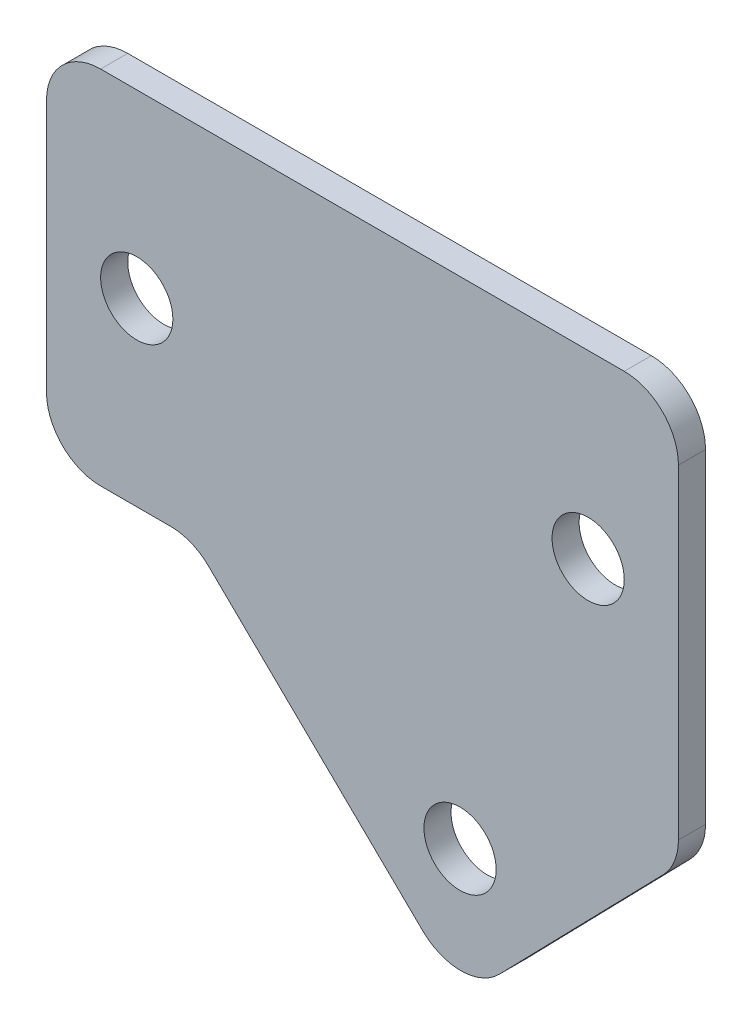
SolidWorks part; units mm, degrees
material "1060 合金"
ref_plane "正面" through (0, 0, 0) normal (0, 0, 1) x (1, 0, 0)
ref_plane "平面" through (0, 0, 0) normal (0, 1, 0) x (1, 0, 0)
ref_plane "右側面" through (0, 0, 0) normal (1, 0, 0) x (0, 0, -1)
sketch "ｽｹｯﾁ1" plane through (0, 0, 0) normal (0, 0, 1) x (1, 0, 0)
  line L0 (-17.5, 7.2592) -> (17.5, 7.2592) construction
  line L1 (-17.5, -17.2592) -> (17.5, -17.2592)
  line L2 (-17.5, -17.2592) -> (-17.5, 17.2592)
  line L3 (-17.5, 17.2592) -> (17.5, 17.2592)
  line L4 (17.5, -17.2592) -> (17.5, 17.2592)
  line L5 (-17.5, -17.2592) -> (17.5, 17.2592) construction
  line L6 (-17.5, 17.2592) -> (17.5, -17.2592) construction
  line L7 (0, 17.2592) -> (0, -17.2592) construction
  line L8 (-12.5, 7.2592) -> (5.4045, -10.1887) construction
  line L9 (-17.5, 5.1502) -> (5.4958, -17.2592)
  line L10 (5.4958, -17.2592) -> (17.5, -4.9409)
  line L11 (-17.5, -2.7408) -> (-9.4025, -2.7408)
  circle A0 centre (-12.5, 7.2592) radius 2
  circle A1 centre (12.5, 7.2592) radius 2
  circle A2 centre (5.4045, -10.1887) radius 2
  point P0 (0, 0)
  dimension "D1" = 25
  dimension "D2" = 10
  dimension "D3" = 5
  dimension "D6" = 4
  dimension "D7" = 5
  dimension "D9" = 5
  dimension "D8" = 5
  dimension "D4" = 135.74
  dimension "D5" = 25
  dimension "D10" = 10
extrude "ﾎﾞｽ - 押し出し1" add sketch "ｽｹｯﾁ1" along normal blind 1.5 contours L9 L10 L4 L3 L2 A2 A0 A1 | L2 L11 L9
fillet "ﾌｨﾚｯﾄ1" radius 3 6 edges at (17.5, 17.2592, 0.75) (17.5, -4.9409, 0.75) (5.4958, -17.2592, 0.75) (-17.5, 17.2592, 0.75) (-9.4025, -2.7408, 0.75) (-17.5, -2.7408, 0.75)
